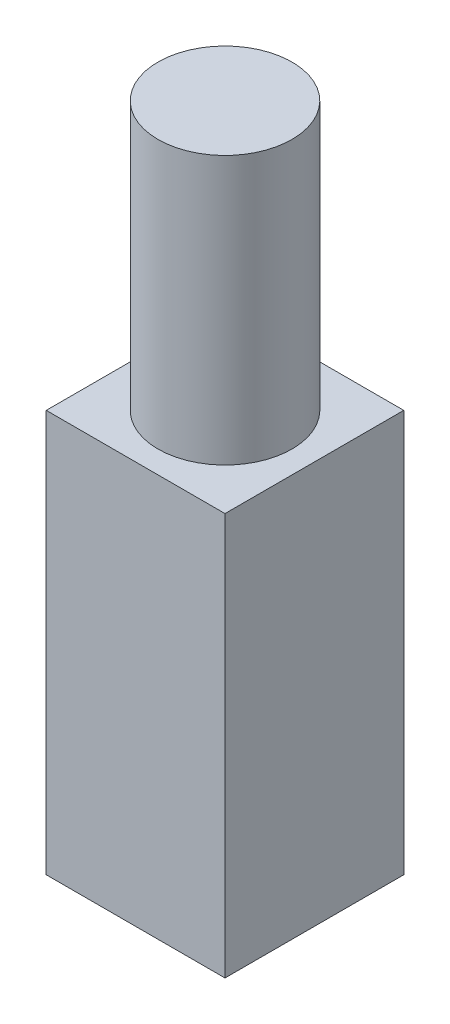
SolidWorks part; units mm, degrees
ref_plane "正面" through (0, 0, 0) normal (0, 0, 1) x (1, 0, 0)
ref_plane "平面" through (0, 0, 0) normal (0, 1, 0) x (1, 0, 0)
ref_plane "右側面" through (0, 0, 0) normal (1, 0, 0) x (0, 0, -1)
sketch "ｽｹｯﾁ3" plane through (0, 0, 0) normal (0, 1, 0) x (1, 0, 0)
  circle A0 centre (0, 0) radius 7.5
  dimension "D1" = 15
extrude "ﾎﾞｽ - 押し出し3" add sketch "ｽｹｯﾁ3" along normal blind 30
sketch "ｽｹｯﾁ4" plane through (0, 0, 0) normal (0, -1, 0) x (1, 0, 0)
  line L1 (10, 10) -> (-10, 10)
  line L2 (10, 10) -> (10, -10)
  line L3 (10, -10) -> (-10, -10)
  line L4 (-10, 10) -> (-10, -10)
  line L5 (10, 10) -> (-10, -10) construction
  line L6 (10, -10) -> (-10, 10) construction
  point P0 (0, 0)
  dimension "D1" = 20
  dimension "D2" = 20
extrude "ﾎﾞｽ - 押し出し4" add sketch "ｽｹｯﾁ4" along normal blind 45
